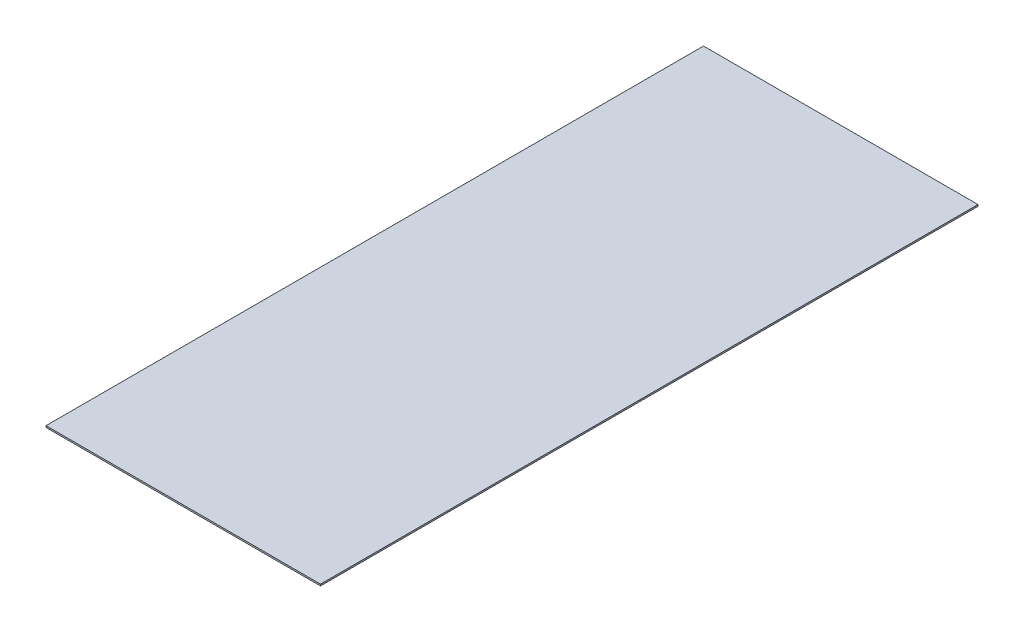
SolidWorks part; units mm, degrees
material "Corrugated Paper"
ref_plane "Front Plane" through (0, 0, 0) normal (0, 0, 1) x (1, 0, 0)
ref_plane "Top Plane" through (0, 0, 0) normal (0, 1, 0) x (1, 0, 0)
ref_plane "Right Plane" through (0, 0, 0) normal (1, 0, 0) x (0, 0, -1)
sketch "Sketch1" plane through (0, 0, 0) normal (0, 1, 0) x (1, 0, 0)
  line L1 (-546.1, -1308.1) -> (546.1, -1308.1)
  line L2 (-546.1, -1308.1) -> (-546.1, 1308.1)
  line L3 (-546.1, 1308.1) -> (546.1, 1308.1)
  line L4 (546.1, -1308.1) -> (546.1, 1308.1)
  line L5 (-546.1, -1308.1) -> (546.1, 1308.1) construction
  line L6 (-546.1, 1308.1) -> (546.1, -1308.1) construction
  point P0 (0, 0)
  dimension "D1" = 2616.2
  dimension "D2" = 1092.2
extrude "Boss-Extrude1" add sketch "Sketch1" along normal blind 6.35
